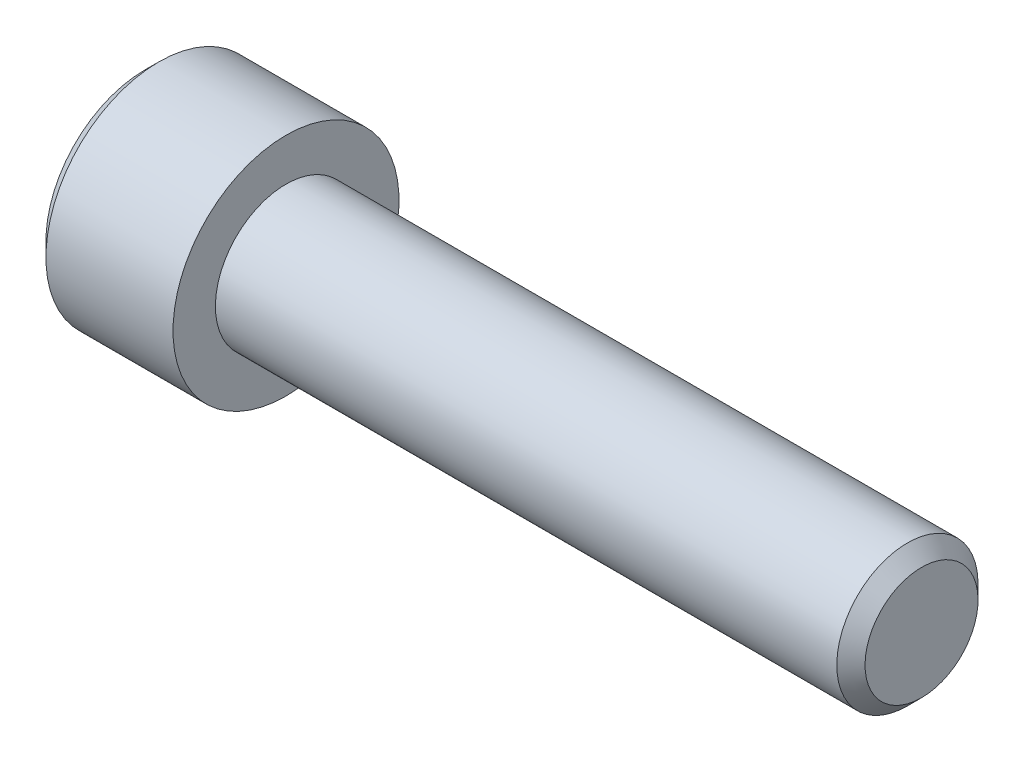
SolidWorks part; units mm, degrees
ref_plane "Front" through (0, 0, 0) normal (0, 0, 1) x (1, 0, 0)
ref_plane "Top" through (0, 0, 0) normal (0, 1, 0) x (1, 0, 0)
ref_plane "Right" through (0, 0, 0) normal (1, 0, 0) x (0, 0, -1)
sketch "Sketch1" plane through (0, 0, 0) normal (0, 0, 1) x (1, 0, 0)
  line L0 (-10, 0) -> (-10, 8)
  line L1 (-10, 0) -> (45, 0)
  line L2 (-10, 8) -> (0, 8)
  line L3 (0, 8) -> (0, 5)
  line L4 (0, 5) -> (45, 5)
  line L6 (45, 5) -> (45, 0)
  line L8 (45, 0) -> (-10, 0) construction
  dimension "D1" = 16
  dimension "D2" = 10
  dimension "D3" = 10
  dimension "D4" = 45
revolve "Revolve1" add sketch "Sketch1" angle 360 about L8
cosmetic thread "Cosmetic Thread1" parameters "D2"=8.619
sketch "Sketch2" plane through (0, 0, 0) normal (0, 0, 1) x (1, 0, 0)
  line L0 (-10, 0) -> (-10, 3.995)
  line L1 (-10, 3.995) -> (-5, 3.995)
  line L2 (-5, 3.995) -> (-3.9295, 0)
  line L3 (-10, 8) -> (-10, -8) construction
  line L4 (-3.9295, 0) -> (-10, 0) construction
  line L5 (-10, 0) -> (-3.9295, 0)
  dimension "D1" = 75
  dimension "D2" = 7.99
  dimension "D3" = 5
revolve "Cut-Revolve1" cut sketch "Sketch2" angle 360 about L4
sketch "Sketch3" plane through (-10, 0, 0) normal (1, 0, 0) x (0, 0, -1)
  line L1 (0, 4.6188) -> (-4, 2.3094)
  line L2 (-4, 2.3094) -> (-4, -2.3094)
  line L3 (-4, -2.3094) -> (0, -4.6188)
  line L4 (0, -4.6188) -> (4, -2.3094)
  line L5 (4, -2.3094) -> (4, 2.3094)
  line L6 (4, 2.3094) -> (0, 4.6188)
  circle A0 centre (0, 0) radius 4 construction
  dimension "D1" = 8
extrude "Cut-Extrude1" cut sketch "Sketch3" along normal blind 5
chamfer "Chamfer1" distance 1 angle 45 2 edges at (-10, -8, 0) (45, -5, 0)
